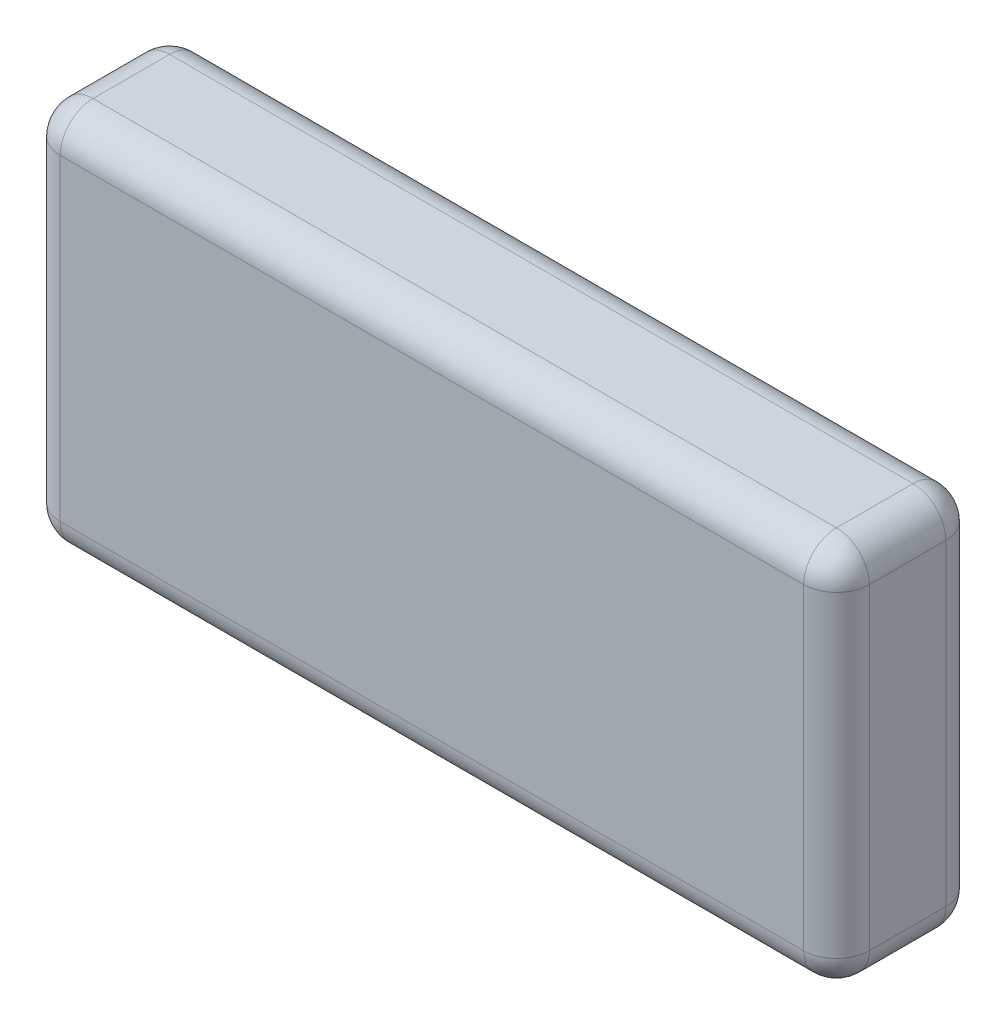
SolidWorks part; units mm, degrees
ref_plane "Plano frontal" through (0, 0, 0) normal (0, 0, 1) x (1, 0, 0)
ref_plane "Plano superior" through (0, 0, 0) normal (0, 1, 0) x (1, 0, 0)
ref_plane "Plano direito" through (0, 0, 0) normal (1, 0, 0) x (0, 0, -1)
sketch "Esboço1" plane through (0, 0, 0) normal (0, 0, 1) x (1, 0, 0)
  line L1 (-27.1122, 25.9843) -> (46.8878, 25.9843)
  line L2 (-27.1122, 25.9843) -> (-27.1122, -9.0157)
  line L3 (-27.1122, -9.0157) -> (46.8878, -9.0157)
  line L4 (46.8878, 25.9843) -> (46.8878, -9.0157)
  dimension "D1" = 74
  dimension "D2" = 35
extrude "Ressalto-extrusão1" add sketch "Esboço1" along normal blind 13
fillet "Filete1" radius 3 12 edges at (-27.1122, 25.9843, 6.5) (9.8878, 25.9843, 0) (9.8878, 25.9843, 13) (46.8878, 25.9843, 6.5) (46.8878, 8.4843, 0) (46.8878, 8.4843, 13) (46.8878, -9.0157, 6.5) (-27.1122, 8.4843, 0) (9.8878, -9.0157, 0) (-27.1122, 8.4843, 13) (9.8878, -9.0157, 13) (-27.1122, -9.0157, 6.5)
